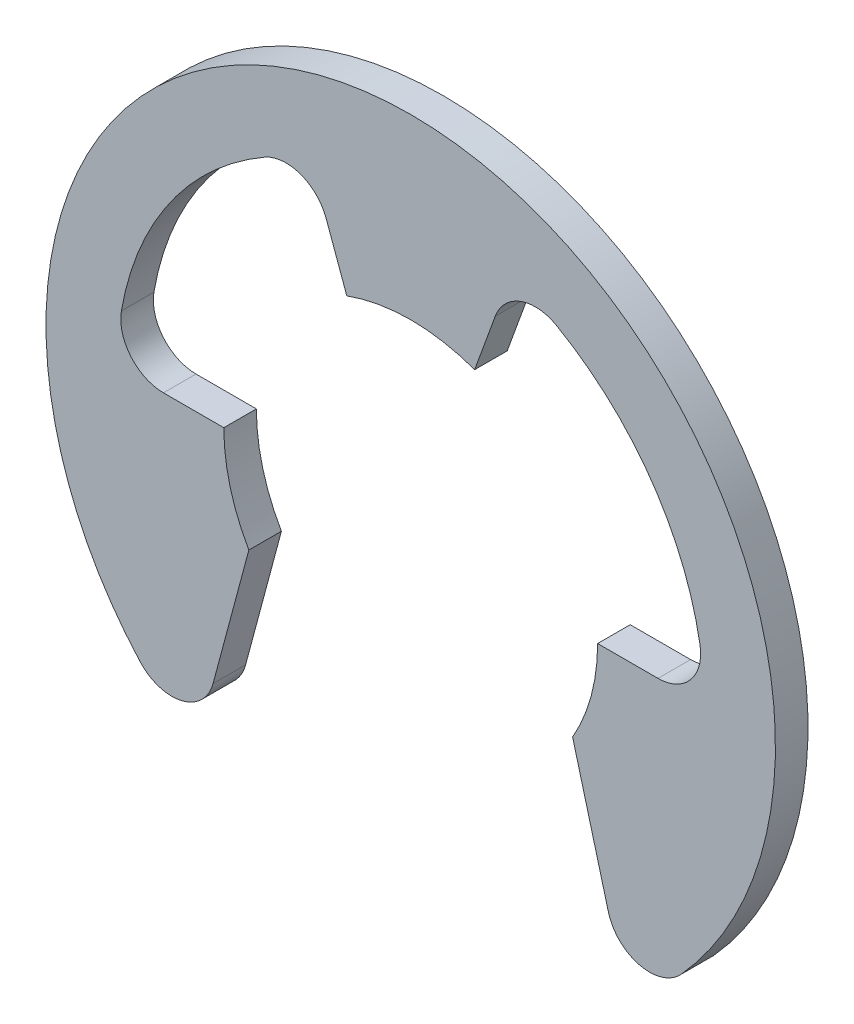
SolidWorks part; units mm, degrees
ref_plane "Plane1" through (0, 0, 0) normal (0, 0, 1) x (1, 0, 0)
ref_plane "Plane2" through (0, 0, 0) normal (0, 1, 0) x (1, 0, 0)
ref_plane "Plane3" through (0, 0, 0) normal (1, 0, 0) x (0, 0, -1)
sketch "Clipboard" plane through (0, 0, 0) normal (0, 0, 1) x (1, 0, 0)
  circle A0 centre (0, 0) radius 7.2898
  circle A1 centre (0, 0) radius 14.224
  dimension "FreeDia" = 14.5796
  dimension "FreeOutsideDia" = 28.448
sketch "BodySke" plane through (0, 0, 0) normal (0, 0, 1) x (1, 0, 0)
  line L0 (0, 0) -> (2.4933, 6.8502) construction
  line L1 (0, 0) -> (-2.4933, 6.8502) construction
  line L2 (0, 0.6037) -> (0, -0.6192) construction
  line L3 (0, 0) -> (1.2813, -0.7398) construction
  line L4 (0, 0) -> (-1.295, -0.7477) construction
  line L5 (0, 0) -> (7.2898, 0) construction
  line L6 (0, 0) -> (-7.2898, 0) construction
  line L7 (6.3132, -3.6449) -> (7.7089, -8.854)
  line L8 (-6.3132, -3.6449) -> (-7.7089, -8.854)
  line L9 (7.2898, 0) -> (9.6436, 0)
  line L10 (-7.2898, 0) -> (-9.6436, 0)
  line L11 (-2.4933, 6.8502) -> (-3.2983, 9.062)
  line L12 (2.4933, 6.8502) -> (3.2983, 9.062)
  arc A0 (-7.2898, 0) -> (-6.3132, -3.6449) centre (0, 0) ccw
  arc A1 (10.5509, -9.5394) -> (-10.5509, -9.5394) centre (0, 0) ccw
  arc A2 (-5.689, 9.9371) -> (-11.2835, 1.9472) centre (0, 0) ccw
  arc A3 (11.2835, 1.9472) -> (5.689, 9.9371) centre (0, 0) ccw
  circle A4 centre (0, 0) radius 14.224 construction
  arc A5 (2.4933, 6.8502) -> (-2.4933, 6.8502) centre (0, 0) ccw
  arc A6 (6.3132, -3.6449) -> (7.2898, 0) centre (0, 0) ccw
  circle A7 centre (0, 0) radius 7.2898 construction
  arc A8 (7.7089, -8.854) -> (10.5509, -9.5394) centre (9.3164, -8.4233) ccw
  arc A9 (-7.7089, -8.854) -> (-10.5509, -9.5394) centre (-9.3164, -8.4233) cw
  arc A10 (-9.6436, 0) -> (-11.2835, 1.9472) centre (-9.6436, 1.6642) cw
  arc A11 (-3.2983, 9.062) -> (-5.689, 9.9371) centre (-4.8621, 8.4928) ccw
  arc A12 (3.2983, 9.062) -> (5.689, 9.9371) centre (4.8621, 8.4928) cw
  arc A13 (9.6436, 0) -> (11.2835, 1.9472) centre (9.6436, 1.6642) ccw
  point P28 (-11.4503, 0)
  point P36 (11.4503, 0)
  dimension "D3" = 1.6642
  dimension "D5" = 11.4503
  dimension "D1" = 40
  dimension "D2" = 30
  dimension "D4" = 15
extrude "Body" add sketch "BodySke" against normal blind 1.27
equation "\"D5@BodySke\" =  ( 3 / 5 * \"FreeOutsideDia@Clipboard\" + 2 / 5 * \"FreeDia@Clipboard\" )  / 2"
equation "\"D3@BodySke\" =  ( \"D5@BodySke\" * 2 - \"FreeDia@Clipboard\" )  / 2 / 2.5"
